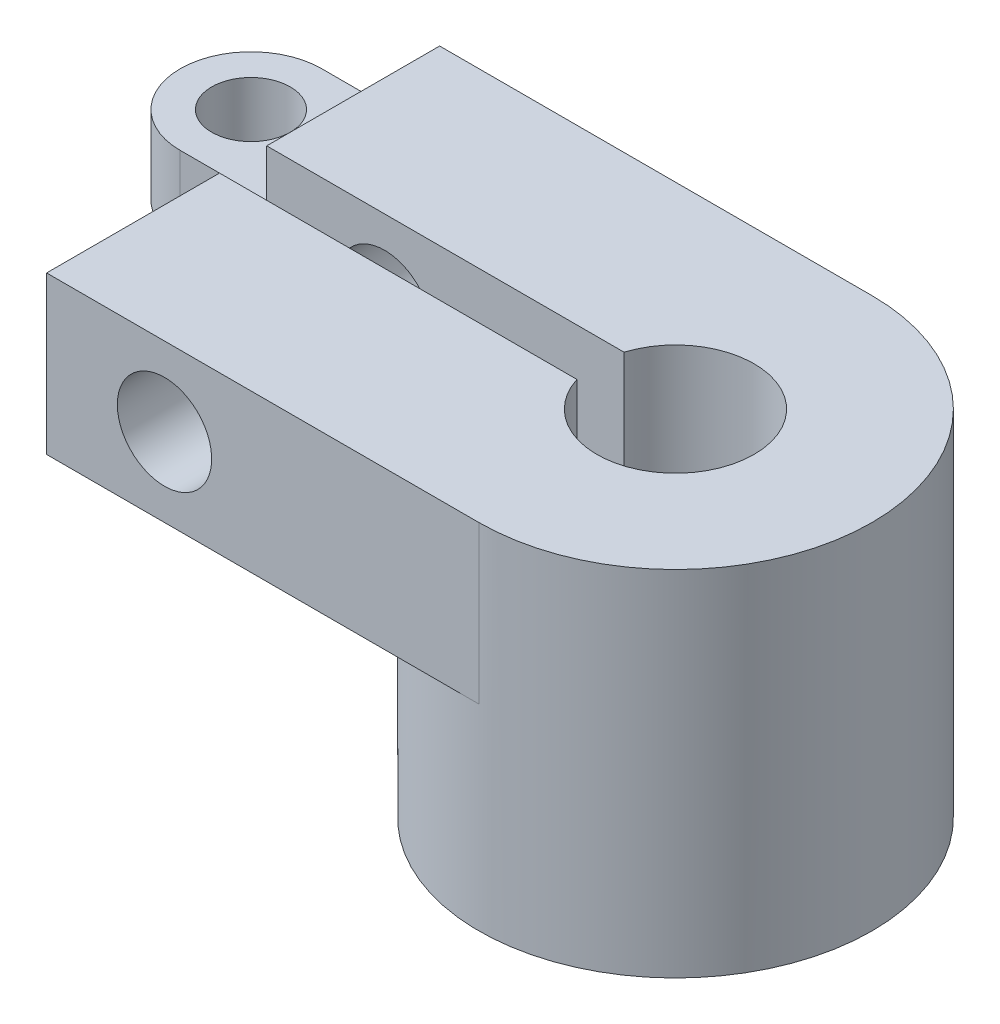
SolidWorks part; units mm, degrees
ref_plane "Front Plane" through (0, 0, 0) normal (0, 0, 1) x (1, 0, 0)
ref_plane "Top Plane" through (0, 0, 0) normal (0, 1, 0) x (1, 0, 0)
ref_plane "Right Plane" through (0, 0, 0) normal (1, 0, 0) x (0, 0, -1)
sketch "Sketch1" plane through (0, 0, 0) normal (0, 1, 0) x (1, 0, 0)
  line L0 (0, 0) -> (-74.5508, 0) construction
  line L1 (0, 25) -> (-55, 25)
  line L2 (-55, 25) -> (-55, 3)
  line L3 (-55, 3) -> (-9.5394, 3)
  line L4 (-55, -3) -> (-9.5394, -3)
  line L5 (-55, -25) -> (-55, -3)
  line L6 (0, -25) -> (-55, -25)
  arc A0 (0, -25) -> (0, 25) centre (0, 0) ccw
  arc A1 (-9.5394, -3) -> (-9.5394, 3) centre (0, 0) ccw
  dimension "D1" = 50
  dimension "D2" = 20
  dimension "D3" = 55
  dimension "D4" = 6
extrude "Boss-Extrude1" add sketch "Sketch1" along normal mid plane 20
sketch "Sketch2" plane through (0, 10, 0) normal (0, 1, 0) x (1, 0, 0)
  line L0 (-9.5394, -3) -> (-55, -3) construction
  line L1 (-55, 3) -> (-9.5394, 3) construction
  line L2 (-9.5394, -3) -> (-24.8193, -3)
  line L3 (-24.8193, 3) -> (-9.5394, 3)
  arc A0 (-24.8193, -3) -> (-24.8193, 3) centre (0, 0) ccw
  arc A1 (0, -25) -> (0, 25) centre (0, 0) ccw construction
  arc A2 (-9.5394, -3) -> (-9.5394, 3) centre (0, 0) ccw construction
  arc A3 (-9.5394, -3) -> (-9.5394, 3) centre (0, 0) ccw
extrude "Boss-Extrude2" add sketch "Sketch2" against normal blind 45
sketch "Sketch3" plane through (0, -10, 0) normal (0, -1, 0) x (1, 0, 0)
  line L0 (0, -25) -> (-55, -25) construction
  line L1 (-55, -7) -> (-70, -7)
  line L2 (-55, -7) -> (-55, -25)
  line L3 (-55, -25) -> (-70, -25)
  line L5 (-55, -25) -> (-55, -3) construction
  arc A0 (-70, -7) -> (-70, -25) centre (-70, -16) ccw
  circle A1 centre (-70, -16) radius 5
  dimension "D1" = 70
  dimension "D3" = 10
  dimension "D2" = 16
extrude "Boss-Extrude3" add sketch "Sketch3" against normal blind 10
hole_wizard "Hole1" positions "Sketch4" profile "Sketch5" legacy end condition through all
sketch "Sketch4" plane through (0, 0, -25) normal (0, 0, -1) x (-1, 0, 0)
  point P0 (40, 0)
  dimension "D1" = 40
sketch "Sketch5" plane through (-40, 0, -25) normal (1, 0, 0) x (0, 1, 0)
  line L0 (0, 0) -> (0, 50)
  line L1 (0, 50) -> (6, 50)
  line L2 (6, 50) -> (6, 0)
  line L3 (6, 0) -> (0, 0)
  line L4 (0, 110) -> (0, -10) construction
  dimension "Diameter" = 12
  dimension "Depth" = 50
